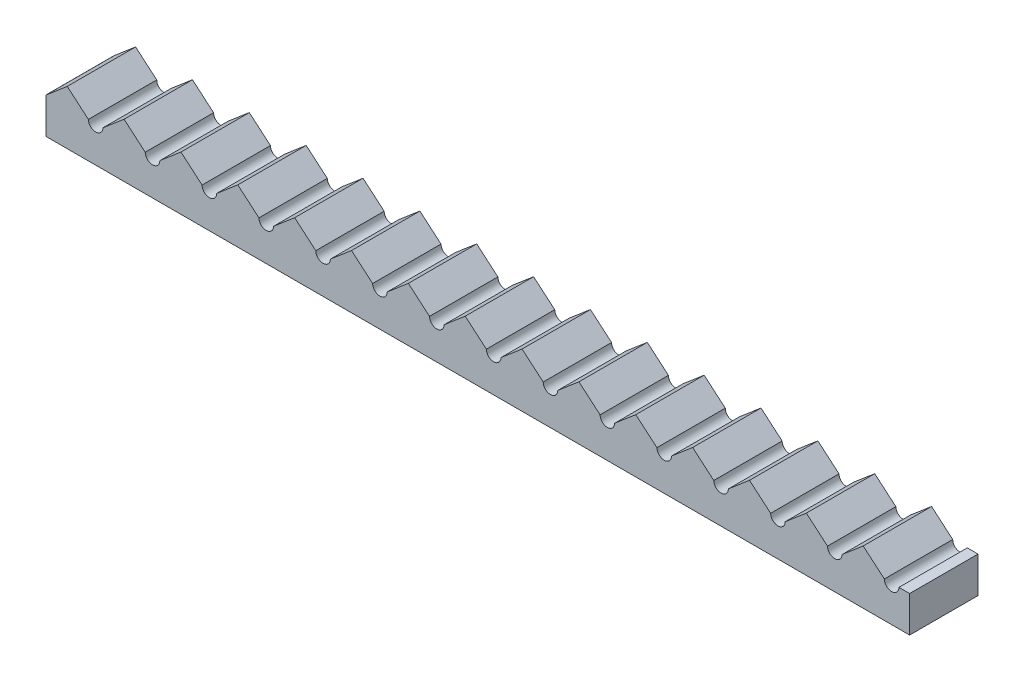
SolidWorks part; units mm, degrees
ref_plane "Front Plane" through (0, 0, 0) normal (0, 0, 1) x (1, 0, 0)
ref_plane "Top Plane" through (0, 0, 0) normal (0, 1, 0) x (1, 0, 0)
ref_plane "Right Plane" through (0, 0, 0) normal (1, 0, 0) x (0, 0, -1)
sketch "Sketch1" plane through (0, 0, 0) normal (0, 0, 1) x (1, 0, 0)
  line L1 (0, 0) -> (-304.8, 0)
  line L2 (0, 0) -> (0, -12.7)
  line L3 (0, -12.7) -> (-304.8, -12.7)
  line L4 (-304.8, 0) -> (-304.8, -12.7)
  dimension "D1" = 12.7
  dimension "D2" = 304.8
extrude "Boss-Extrude1" add sketch "Sketch1" along normal blind 24.13
sketch "Sketch3" plane through (0, 0, 24.13) normal (0, 0, 1) x (1, 0, 0)
  circle A0 centre (-26.416, 0) radius 2.5717
  circle A1 centre (-46.482, 0) radius 2.5717
  circle A2 centre (-66.548, 0) radius 2.5717
  circle A3 centre (-86.614, 0) radius 2.5717
  circle A4 centre (-106.68, 0) radius 2.5717
  circle A5 centre (-126.746, 0) radius 2.5717
  circle A6 centre (-146.812, 0) radius 2.5717
  circle A7 centre (-166.878, 0) radius 2.5718
  circle A8 centre (-186.944, 0) radius 2.5717
  circle A9 centre (-6.35, 0) radius 2.5717
  circle A10 centre (-207.01, 0) radius 2.5718
  circle A11 centre (-227.076, 0) radius 2.5717
  circle A12 centre (-247.142, 0) radius 2.5718
  circle A13 centre (-267.208, 0) radius 2.5718
  circle A14 centre (-287.274, 0) radius 2.5718
  dimension "D1" = 15
  dimension "D2" = 20.066
  dimension "D3" = 6.35
extrude "Cut-Extrude1" cut sketch "Sketch3" against normal blind 39.624
sketch "Sketch4" plane through (0, 0, 0) normal (0, 0, -1) x (-1, 0, 0)
  line L0 (8.9217, 0) -> (23.8443, 0)
  line L1 (23.8443, 0) -> (16.383, 6.35)
  line L2 (16.383, 6.35) -> (8.9217, 0)
  line L3 (28.9877, 0) -> (36.449, 6.35)
  line L4 (36.449, 6.35) -> (43.9103, 0)
  line L5 (28.9877, 0) -> (43.9103, 0)
  line L6 (56.515, 6.35) -> (63.9763, 0)
  line L7 (49.0537, 0) -> (63.9763, 0)
  line L8 (49.0537, 0) -> (56.515, 6.35)
  line L9 (76.581, 6.35) -> (84.0422, 0)
  line L10 (69.1197, 0) -> (84.0422, 0)
  line L11 (69.1197, 0) -> (76.581, 6.35)
  line L12 (96.647, 6.35) -> (104.1082, 0)
  line L13 (89.1857, 0) -> (104.1082, 0)
  line L14 (89.1857, 0) -> (96.647, 6.35)
  line L15 (116.713, 6.35) -> (124.1742, 0)
  line L16 (109.2517, 0) -> (124.1742, 0)
  line L17 (109.2517, 0) -> (116.713, 6.35)
  line L18 (136.779, 6.35) -> (144.2402, 0)
  line L19 (129.3177, 0) -> (144.2402, 0)
  line L20 (129.3177, 0) -> (136.779, 6.35)
  line L21 (156.845, 6.35) -> (164.3062, 0)
  line L22 (149.3837, 0) -> (164.3062, 0)
  line L23 (149.3837, 0) -> (156.845, 6.35)
  line L24 (176.911, 6.35) -> (184.3722, 0)
  line L25 (169.4497, 0) -> (184.3722, 0)
  line L26 (169.4497, 0) -> (176.911, 6.35)
  line L27 (196.977, 6.35) -> (204.4382, 0)
  line L28 (189.5157, 0) -> (204.4382, 0)
  line L29 (189.5157, 0) -> (196.977, 6.35)
  line L30 (217.043, 6.35) -> (224.5042, 0)
  line L31 (209.5817, 0) -> (224.5042, 0)
  line L32 (209.5817, 0) -> (217.043, 6.35)
  line L33 (237.109, 6.35) -> (244.5702, 0)
  line L34 (229.6477, 0) -> (244.5702, 0)
  line L35 (229.6477, 0) -> (237.109, 6.35)
  line L36 (257.175, 6.35) -> (264.6362, 0)
  line L37 (249.7137, 0) -> (264.6362, 0)
  line L38 (249.7137, 0) -> (257.175, 6.35)
  line L39 (277.241, 6.35) -> (284.7022, 0)
  line L40 (269.7797, 0) -> (284.7022, 0)
  line L41 (269.7797, 0) -> (277.241, 6.35)
  line L42 (297.307, 6.35) -> (304.7682, 0)
  line L43 (289.8457, 0) -> (304.7682, 0)
  line L44 (289.8457, 0) -> (297.307, 6.35)
  dimension "D1" = 6.35
  dimension "D2" = 6.35
  dimension "D3" = 14
extrude "Boss-Extrude2" add sketch "Sketch4" against normal up to surface (24.13 mm away) contours L41 L39 L40
